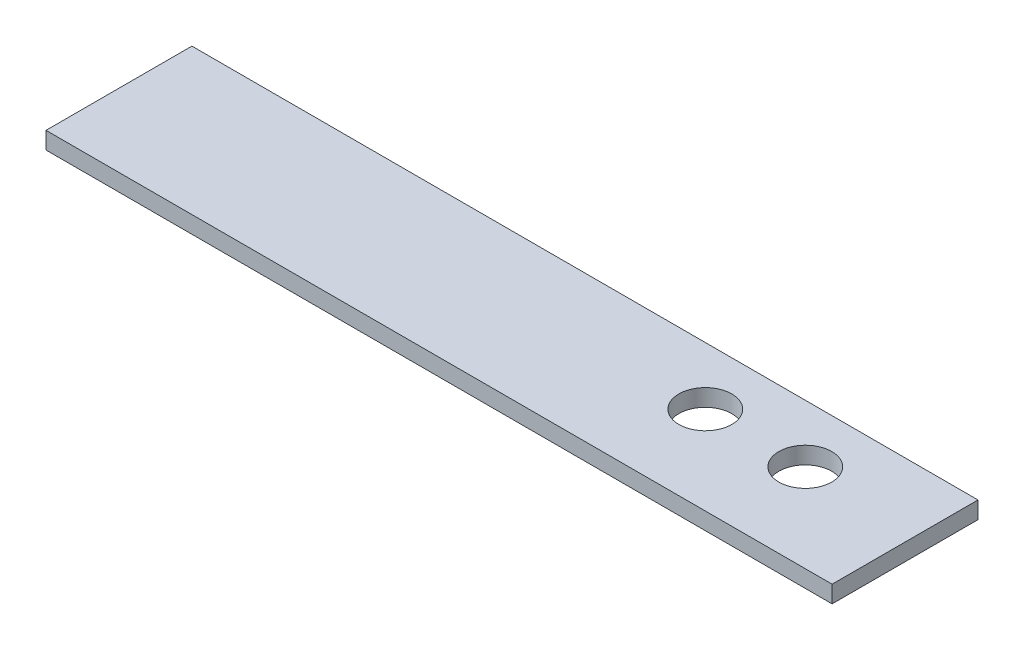
SolidWorks part; units mm, degrees
ref_plane "Front Plane" through (0, 0, 0) normal (0, 0, 1) x (1, 0, 0)
ref_plane "Top Plane" through (0, 0, 0) normal (0, 1, 0) x (1, 0, 0)
ref_plane "Right Plane" through (0, 0, 0) normal (1, 0, 0) x (0, 0, -1)
sketch "Sketch1" plane through (0, 0, 0) normal (0, 1, 0) x (1, 0, 0)
  line L1 (-62.8005, 146.8212) -> (813.4995, 146.8212)
  line L2 (-62.8005, 146.8212) -> (-62.8005, -15.8182)
  line L3 (-62.8005, -15.8182) -> (813.4995, -15.8182)
  line L4 (813.4995, 146.8212) -> (813.4995, -15.8182)
extrude "Boss-Extrude1" add sketch "Sketch1" along normal blind 19.05 contours L2 L1 L4 L3
sketch "Sketch2" plane through (0, 19.05, 0) normal (0, 1, 0) x (1, 0, 0)
  circle A0 centre (685.2403, 82.5679) radius 29.5
  point P2 (0, 0)
sketch "Sketch3" plane through (0, 19.05, 0) normal (0, 1, 0) x (1, 0, 0)
  circle A0 centre (573.9059, 82.4588) radius 29.5
  point P2 (0, 0)
extrude "Cut-Extrude1" cut sketch "Sketch3" against normal blind 19.05 contours A0
extrude "Cut-Extrude2" cut sketch "Sketch2" against normal blind 19.05
